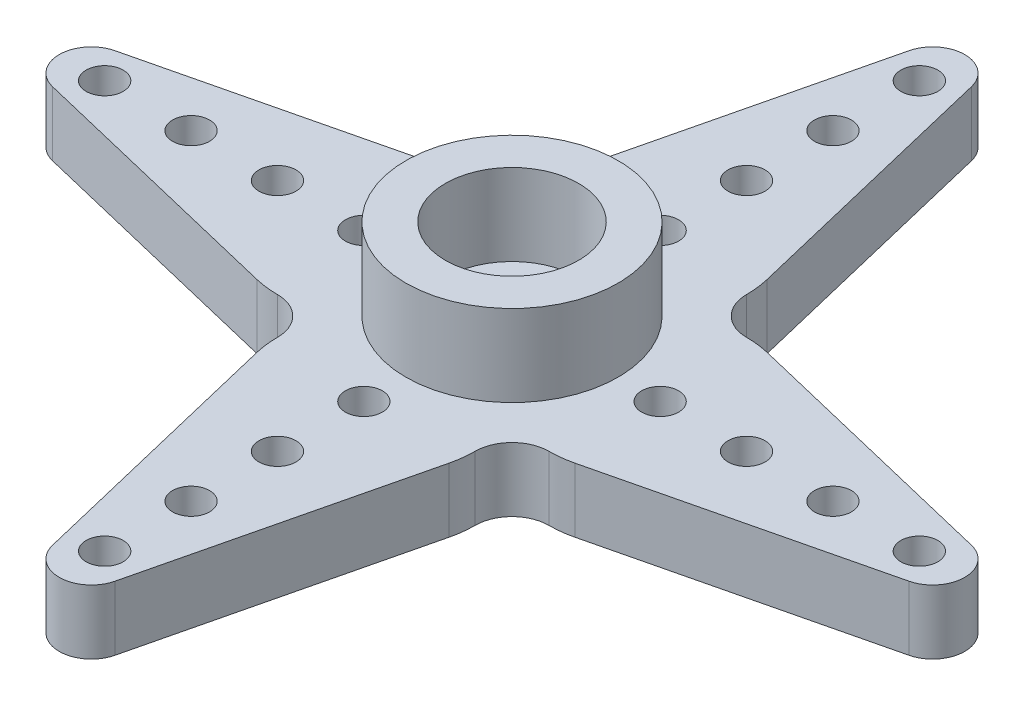
SolidWorks part; units mm, degrees
ref_plane "Front Plane" through (0, 0, 0) normal (0, 0, 1) x (1, 0, 0)
ref_plane "Top Plane" through (0, 0, 0) normal (0, 1, 0) x (1, 0, 0)
ref_plane "Right Plane" through (0, 0, 0) normal (1, 0, 0) x (0, 0, -1)
sketch "Sketch1" plane through (0, 0, 0) normal (0, 1, 0) x (1, 0, 0)
  line L0 (-1.2639, 17.3442) -> (-3.889, 6.4359)
  line L1 (1.2639, 17.3442) -> (3.889, 6.4359)
  line L2 (17.3442, 1.2639) -> (6.4359, 3.889)
  line L3 (17.3442, -1.2639) -> (6.4359, -3.889)
  line L4 (1.2639, -17.3442) -> (3.889, -6.4359)
  line L5 (-1.2639, -17.3442) -> (-3.889, -6.4359)
  line L6 (-17.3442, -1.2639) -> (-6.4359, -3.889)
  line L7 (-17.3442, 1.2639) -> (-6.4359, 3.889)
  line L8 (4, 5.5) -> (4, 0) construction
  arc A0 (1.2639, 17.3442) -> (-1.2639, 17.3442) centre (0, 17.04) ccw
  arc A1 (3.889, 6.4359) -> (4, 5.5) centre (0, 5.5) cw
  arc A2 (4, 5.5) -> (5.5, 4) centre (5.5, 5.5) ccw
  arc A3 (-3.889, 6.4359) -> (-4, 5.5) centre (0, 5.5) ccw
  arc A4 (17.3442, -1.2639) -> (17.3442, 1.2639) centre (17.04, 0) ccw
  arc A5 (6.4359, -3.889) -> (5.5, -4) centre (5.5, 0) cw
  arc A6 (5.5, -4) -> (4, -5.5) centre (5.5, -5.5) ccw
  arc A7 (6.4359, 3.889) -> (5.5, 4) centre (5.5, 0) ccw
  arc A8 (-1.2639, -17.3442) -> (1.2639, -17.3442) centre (0, -17.04) ccw
  arc A9 (-3.889, -6.4359) -> (-4, -5.5) centre (0, -5.5) cw
  arc A10 (-4, -5.5) -> (-5.5, -4) centre (-5.5, -5.5) ccw
  arc A11 (3.889, -6.4359) -> (4, -5.5) centre (0, -5.5) ccw
  arc A12 (-17.3442, 1.2639) -> (-17.3442, -1.2639) centre (-17.04, 0) ccw
  arc A13 (-6.4359, 3.889) -> (-5.5, 4) centre (-5.5, 0) cw
  arc A14 (-5.5, 4) -> (-4, 5.5) centre (-5.5, 5.5) ccw
  arc A15 (-6.4359, -3.889) -> (-5.5, -4) centre (-5.5, 0) ccw
  point P1 (4, 0)
  point P7 (5.5, 0)
  point P17 (5.5, 0)
  point P22 (6.4359, 4)
  point P26 (5.5, 3.889)
  point P27 (5.5, 5.5)
  point P35 (17.04, 0)
  point P44 (6.4359, -4)
  point P46 (5.5, -3.889)
  point P48 (0, 0)
  point P49 (0, 0)
  point P50 (4, -6.4359)
  point P51 (5.5, -5.5)
  point P52 (0, 0)
  point P53 (0, 0)
  dimension "D1" = 2.6
  dimension "D3" = 4
  dimension "D4" = 1.5
  dimension "D2" = 17.04
  dimension "D5" = 4
extrude "Boss-Extrude1" add sketch "Sketch1" along normal blind 2.6
sketch "Sketch2" plane through (0, 2.6, 0) normal (0, 1, 0) x (1, 0, 0)
  circle A0 centre (0, 0) radius 1.5
  dimension "D1" = 3
extrude "Cut-Extrude1" cut sketch "Sketch2" against normal through all
sketch "Sketch3" plane through (0, 2.6, 0) normal (0, 1, 0) x (1, 0, 0)
  circle A0 centre (0, 6) radius 0.75
  circle A1 centre (0, 0) radius 1.5 construction
  point P4 (0, 0)
  dimension "D1" = 1.5
  dimension "D2" = 6
extrude "Cut-Extrude2" cut sketch "Sketch3" against normal through all contours A0
pattern_linear "LPattern1" count 4 spacing 3.5 along (0, 0, -1) of "Cut-Extrude2"
pattern_circular "CirPattern1" count 4 every 90 about axis through (0, 0, 0) along (0, 1, 0) of "LPattern1", "Cut-Extrude2"
sketch "Sketch4" plane through (0, 2.6, 0) normal (0, 1, 0) x (1, 0, 0)
  circle A0 centre (0, 0) radius 2.7
  circle A1 centre (0, 0) radius 4.3
  dimension "D1" = 5.4
  dimension "D2" = 8.6
extrude "Boss-Extrude2" add sketch "Sketch4" along normal blind 3.3
sketch "Sketch5" plane through (0, 0, 0) normal (0, -1, 0) x (1, 0, 0)
  circle A0 centre (0, 0) radius 2.2
  circle A1 centre (0, 0) radius 2.7
  circle A3 centre (0, 0) radius 4.3
  circle M17 centre (0, 0) radius 1.5
  dimension "D1" = 4.4
  dimension "D2" = 5.4
  dimension "D3" = 8.6
extrude "Cut-Extrude3" cut sketch "Sketch5" against normal blind 1 contours A0 M17 | A3 A1
